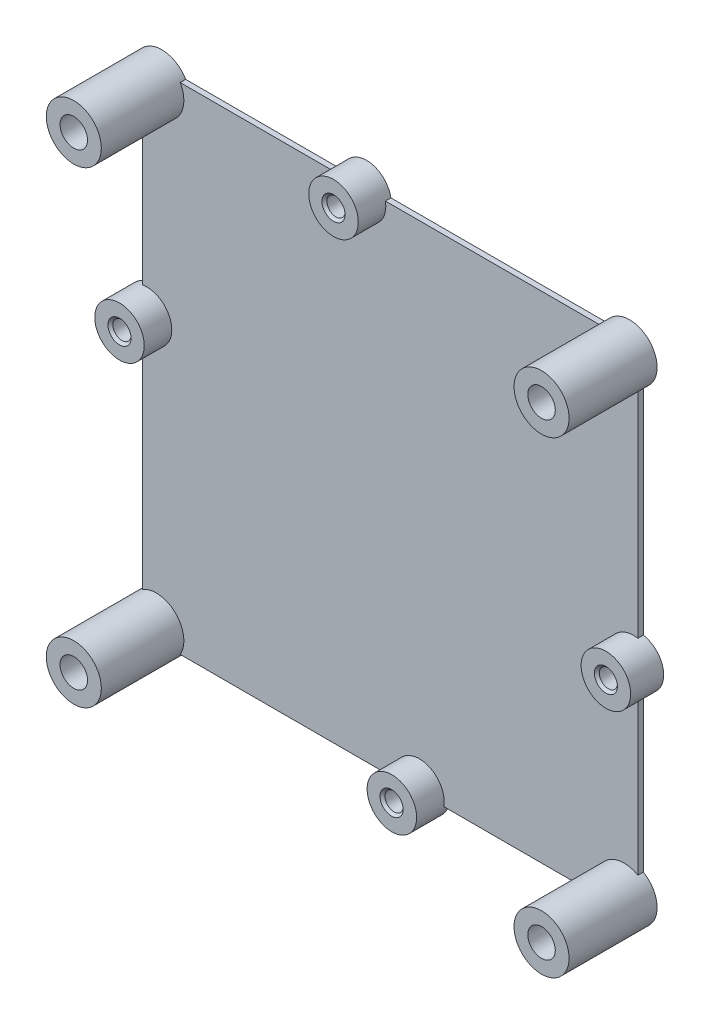
SolidWorks part; units mm, degrees
ref_plane "Ebene vorne" through (0, 0, 0) normal (0, 0, 1) x (1, 0, 0)
ref_plane "Ebene oben" through (0, 0, 0) normal (0, 1, 0) x (1, 0, 0)
ref_plane "Ebene rechts" through (0, 0, 0) normal (1, 0, 0) x (0, 0, -1)
sketch "Skizze1" plane through (0, 0, 0) normal (0, 0, 1) x (1, 0, 0)
  line L1 (-45, 45) -> (45, 45)
  line L2 (-45, 45) -> (-45, -45)
  line L3 (-45, -45) -> (45, -45)
  line L4 (45, 45) -> (45, -45)
  line L5 (-45, 45) -> (45, -45) construction
  line L6 (-45, -45) -> (45, 45) construction
  point P0 (0, 0)
  dimension "D1" = 90
  dimension "D2" = 90
extrude "Aufsatz-Linear austragen1" add sketch "Skizze1" along normal blind 1
sketch "Skizze12" plane through (0, 0, 1) normal (0, 0, 1) x (1, 0, 0)
  line L0 (45, 45) -> (-45, 45) construction
  line L6 (-45, 45) -> (-45, -45) construction
  circle A0 centre (-42.5, 42.5) radius 5
  circle A1 centre (-42.5, 42.5) radius 2.5
  point P0 (0, 0)
  dimension "D3" = 5
  dimension "D4" = 10
  dimension "D1" = 2.5
  dimension "D2" = 2.5
  dimension "D6" = 2.5
  dimension "D5" = 2.5
extrude "Aufsatz-Linear austragen2" add sketch "Skizze12" along normal blind 15 and the other way blind 1 contours A0
sketch "Skizze13" plane through (0, 0, 16) normal (0, 0, 1) x (1, 0, 0)
  circle A0 centre (-42.5, 42.5) radius 2.5
extrude "Schnitt-Linear austragen6" cut sketch "Skizze13" against normal blind 100
pattern_linear "Lineares Muster1" count 2 spacing 85 along (1, 0, 0) count 2 spacing 85 along (0, -1, 0) of "Aufsatz-Linear austragen2", "Schnitt-Linear austragen6"
sketch "Skizze16" plane through (0, 0, 1) normal (0, 0, 1) x (1, 0, 0)
  line L0 (-51.2652, 5.3033) -> (5.3033, -51.2652)
  line L1 (-51.2652, 5.3033) -> (-5.3033, 51.2652)
  line L2 (5.3033, -51.2652) -> (51.2652, -5.3033)
  line L3 (-5.3033, 51.2652) -> (51.2652, -5.3033)
  line L4 (-51.2652, 5.3033) -> (51.2652, -5.3033) construction
  line L5 (5.3033, -51.2652) -> (-5.3033, 51.2652) construction
  line L6 (-38.1699, -45) -> (38.1699, -45) construction
  line L7 (-28.2843, 28.2843) -> (28.2843, -28.2843) construction
  line L8 (22.981, 22.981) -> (-22.981, -22.981) construction
  circle A0 centre (44.1942, -5.3033) radius 4.5
  circle A1 centre (5.3033, -44.1942) radius 4.5
  circle A2 centre (-44.1942, 5.3033) radius 4.5
  circle A3 centre (-5.3033, 44.1942) radius 4.5
  point P1 (0, 0)
  dimension "D4" = 9
  dimension "D5" = 27.5
  dimension "D6" = 35
  dimension "D7" = 9
  dimension "D8" = 9
  dimension "D9" = 9
  dimension "D10" = 27.5
  dimension "D11" = 27.5
  dimension "D12" = 27.5
  dimension "D13" = 35
  dimension "D14" = 35
  dimension "D15" = 35
  dimension "D1" = 45
  dimension "D2" = 65
  dimension "D3" = 80
extrude "Aufsatz-Linear austragen3" add sketch "Skizze16" along normal blind 5 and the other way blind 1 contours A2 | A3 | A1 | A0
sketch "Skizze17" plane through (0, 0, 6) normal (0, 0, 1) x (1, 0, 0)
  circle A0 centre (-44.1942, 5.3033) radius 1.65
  circle A1 centre (-5.3033, 44.1942) radius 1.65
  circle A2 centre (44.1942, -5.3033) radius 1.65
  circle A4 centre (5.2436, -44.1544) radius 1.65
  dimension "D1" = 3.3
  dimension "D2" = 3.3
  dimension "D3" = 3.3
  dimension "D4" = 3.3
hole_wizard "Formsenkung für M3 Linsensenkschraube mit Schlitz1" positions "Skizze18" profile "Skizze19" countersink size "M3" standard "DIN"
sketch "Skizze18" plane through (0, 0, 6) normal (0, 0, 1) x (1, 0, 0)
  point P0 (5.2436, -44.1544)
  point P3 (44.1942, -5.3033)
  point P6 (-5.3033, 44.1942)
  point P9 (-44.1942, 5.3033)
sketch "Skizze19" plane through (5.2436, -44.1544, 6) normal (1, 0, 0) x (0, -1, 0)
  line L0 (0, 0) -> (0, 20.9914)
  line L1 (0, 20.9914) -> (1.65, 20)
  line L2 (1.65, 20) -> (1.65, 0.45)
  line L3 (1.65, 0.45) -> (2.1, 0)
  line L5 (2.1, 0) -> (0, 0)
  line L6 (-1.65, 0.45) -> (-2.1, 0) construction
  line L10 (0, 20.9914) -> (-1.65, 20) construction
  line L11 (0, -6.35) -> (0, 107.95) construction
  dimension "Bohrerdurchmesser" = 3.3
  dimension "Bohrungstiefe" = 20
  dimension "Senkdurchmesser (Oben)" = 4.2
  dimension "Senkwinkel (Oben)" = 90
  dimension "Spitzenwinkel" = 118
